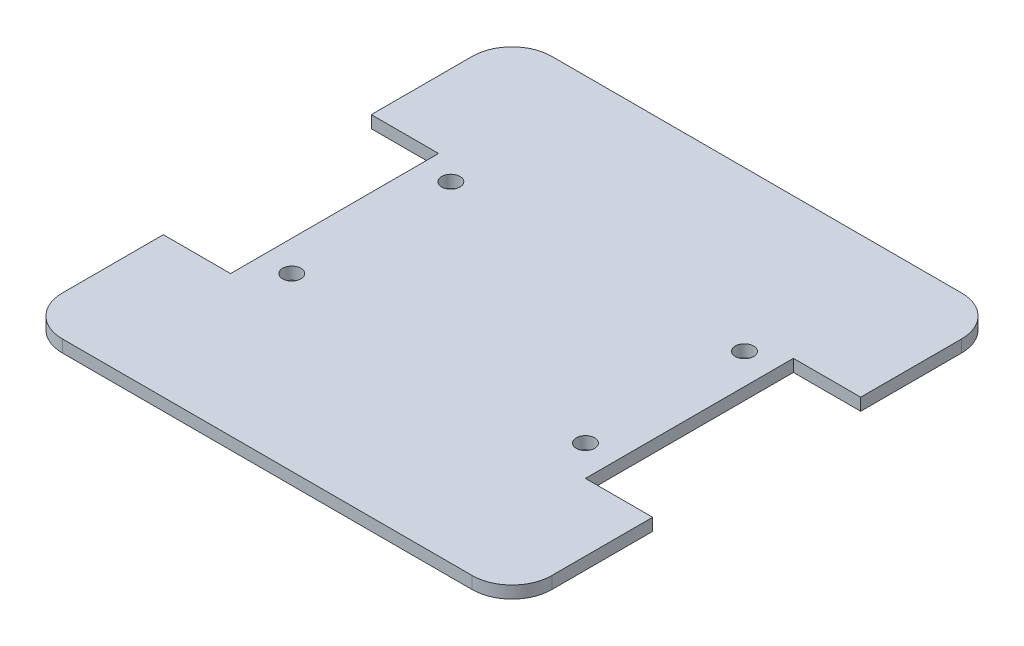
SolidWorks part; units mm, degrees
material "Acrylic (Medium-high impact)"
ref_plane "Front Plane" through (0, 0, 0) normal (0, 0, 1) x (1, 0, 0)
ref_plane "Top Plane" through (0, 0, 0) normal (0, 1, 0) x (1, 0, 0)
ref_plane "Right Plane" through (0, 0, 0) normal (1, 0, 0) x (0, 0, -1)
sketch "Sketch1" plane through (0, 0, 0) normal (0, 1, 0) x (1, 0, 0)
  line L25 (6.5, 0) -> (73.5, 0)
  line L26 (80, 6.5) -> (80, 23)
  line L27 (73.5, 80) -> (6.5, 80)
  line L28 (0, 73.5) -> (0, 57)
  line L29 (11, 23) -> (0, 23)
  line L30 (11, 23) -> (11, 57)
  line L31 (11, 57) -> (0, 57)
  line L32 (0, 23) -> (0, 6.5)
  line L33 (40, 80) -> (40, 0) construction
  line L34 (69, 23) -> (69, 57)
  line L35 (69, 23) -> (80, 23)
  line L36 (69, 57) -> (80, 57)
  line L37 (80, 57) -> (80, 73.5)
  line L38 (16, 54) -> (16, 28) construction
  arc A23 (6.5, 0) -> (0, 6.5) centre (6.5, 6.5) cw
  arc A24 (80, 6.5) -> (73.5, 0) centre (73.5, 6.5) cw
  arc A25 (73.5, 80) -> (80, 73.5) centre (73.5, 73.5) cw
  arc A26 (6.5, 80) -> (0, 73.5) centre (6.5, 73.5) ccw
  circle A27 centre (16, 54) radius 1.5
  circle A28 centre (16, 28) radius 1.5
  circle A29 centre (64, 28) radius 1.5
  circle A30 centre (64, 54) radius 1.5
  point P0 (11, 40)
  point P3 (0, 0)
  point P28 (0, 0)
  point P38 (11, 23)
  point P49 (80, 0)
  point P52 (80, 80)
  point P57 (40, 0)
  point P60 (40, 80)
  point P67 (16, 54)
  dimension "D5" = 6.5
  dimension "D17" = 3
  dimension "D18" = 3
  dimension "D2" = 80
  dimension "D3" = 80
  dimension "D8" = 11
  dimension "D9" = 23
  dimension "D10" = 34
  dimension "D11" = 5
  dimension "D13" = 26
  dimension "D15" = 26
extrude "Boss-Extrude1" add sketch "Sketch1" along normal blind 2
